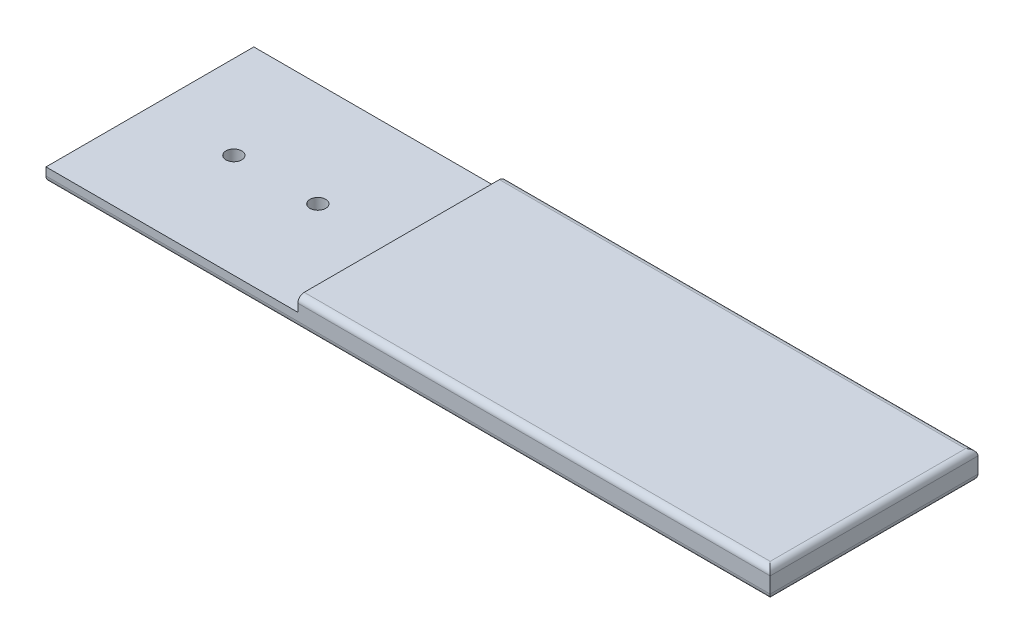
SolidWorks part; units mm, degrees
ref_plane "Front Plane" through (0, 0, 0) normal (0, 0, 1) x (1, 0, 0)
ref_plane "Top Plane" through (0, 0, 0) normal (0, 1, 0) x (1, 0, 0)
ref_plane "Right Plane" through (0, 0, 0) normal (1, 0, 0) x (0, 0, -1)
sketch "Sketch1" plane through (0, 0, 0) normal (0, 1, 0) x (1, 0, 0)
  line L1 (-32.5899, -20.5484) -> (197.4101, -20.5484)
  line L2 (-32.5899, -20.5484) -> (-32.5899, 45.4516)
  line L3 (-32.5899, 45.4516) -> (197.4101, 45.4516)
  line L4 (197.4101, -20.5484) -> (197.4101, 45.4516)
  dimension "D1" = 230
  dimension "D2" = 66
extrude "Boss-Extrude1" add sketch "Sketch1" along normal blind 4.5
sketch "Sketch2" plane through (0, 0, 0) normal (0, -1, 0) x (1, 0, 0)
  line L0 (-32.5899, 20.5484) -> (-32.5899, -45.4516) construction
  line L1 (-32.5899, -12.4516) -> (-5.9232, -12.4516)
  line L2 (-5.9232, -12.4516) -> (20.7435, -12.4516)
  dimension "D1" = 26.6667
  dimension "D2" = 26.6667
ref_plane "Plane1" through (0, -10, 0) normal (0, -1, 0) x (-1, 0, 0)
ref_plane "Plane4" through (0, 14.5, 0) normal (0, 1, 0) x (1, 0, 0)
sketch "Sketch11" plane through (0, 4.5, 0) normal (0, 1, 0) x (1, 0, 0)
  line L0 (-32.5899, 45.4516) -> (47.4101, 45.4516)
  line L1 (197.4101, 45.4516) -> (-32.5899, 45.4516) construction
  line L3 (47.4101, 45.4516) -> (197.4101, 45.4516)
  line L4 (47.4101, 45.4516) -> (47.4101, -20.5484)
  line L5 (47.4101, -20.5484) -> (197.4101, -20.5484)
  line L6 (197.4101, 45.4516) -> (197.4101, -20.5484)
  line M5 (-32.5899, -20.5484) -> (197.4101, -20.5484)
  line M6 (197.4101, -20.5484) -> (197.4101, 45.4516)
  line M7 (197.4101, 45.4516) -> (-32.5899, 45.4516)
  dimension "D1" = 80
extrude "Boss-Extrude2" add sketch "Sketch11" along normal blind 4.5 contours L4 M7 M5 M6
sketch "Sketch16" plane through (0, 0, 0) normal (0, -1, 0) x (1, 0, 0)
  circle A0 centre (-5.9232, -12.4516) radius 6.12
  circle A1 centre (20.7435, -12.4516) radius 6.12
  dimension "D1" = 12.24
  dimension "D2" = 12.24
hole_wizard "Ø5.0mm Dowel Hole1" positions "Sketch17" profile "Sketch18" hole size "Ø5.0" standard "ANSI Metric" end condition through all
sketch "Sketch17" plane through (0, 0, 0) normal (0, -1, 0) x (-1, 0, 0)
  point P0 (5.9232, 12.4516)
  point P3 (-20.7435, 12.4516)
sketch "Sketch18" plane through (-5.9232, 0, -12.4516) normal (1, 0, 0) x (0, 0, -1)
  line L0 (0, 0) -> (0, 9)
  line L1 (0, 9) -> (2.5, 9)
  line L2 (2.5, 9) -> (2.5, 0)
  line L5 (2.5, 0) -> (0, 0)
  line L11 (0, -6.35) -> (0, 107.95) construction
  dimension "Thru Hole Dia." = 5
  dimension "Thru Hole Depth" = 9
fillet "Fillet1" radius 2 6 edges at (122.4101, 9, 20.5484) (197.4101, 9, -12.4516) (122.4101, 9, -45.4516) (82.4101, 0, -45.4516) (82.4101, 0, 20.5484) (197.4101, 0, -12.4516)
